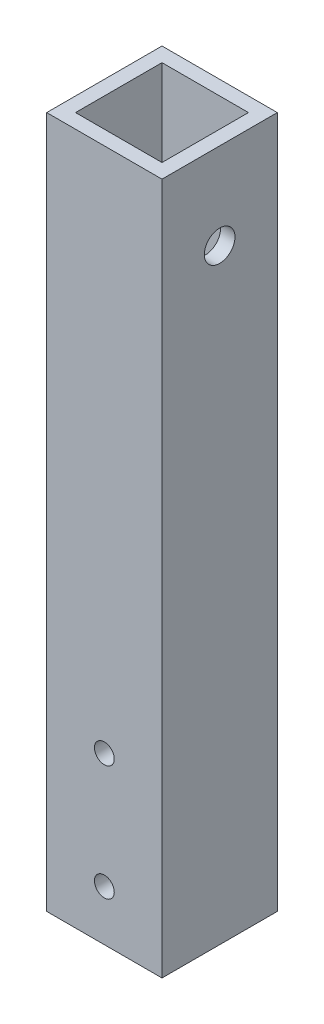
SolidWorks part; units mm, degrees
ref_plane "Front Plane" through (0, 0, 0) normal (0, 0, 1) x (1, 0, 0)
ref_plane "Top Plane" through (0, 0, 0) normal (0, 1, 0) x (1, 0, 0)
ref_plane "Right Plane" through (0, 0, 0) normal (1, 0, 0) x (0, 0, -1)
sketch "Sketch1" plane through (0, 0, 0) normal (0, 1, 0) x (1, 0, 0)
  line L0 (-12.7, 12.7) -> (12.7, 12.7)
  line L1 (-9.525, -9.525) -> (9.525, -9.525)
  line L2 (-9.525, -9.525) -> (-9.525, 9.525)
  line L3 (-9.525, 9.525) -> (9.525, 9.525)
  line L4 (9.525, -9.525) -> (9.525, 9.525)
  line L5 (-9.525, -9.525) -> (9.525, 9.525) construction
  line L6 (-9.525, 9.525) -> (9.525, -9.525) construction
  line L7 (12.7, -12.7) -> (12.7, 12.7)
  line L8 (-12.7, -12.7) -> (12.7, -12.7)
  line L9 (-12.7, -12.7) -> (-12.7, 12.7)
  point P0 (0, 0)
  dimension "D2" = 25.4
  dimension "D1" = 3.175
extrude "Boss-Extrude1" add sketch "Sketch1" along normal blind 152.4
sketch "Sketch2" plane through (0, 0, 12.7) normal (0, 0, 1) x (1, 0, 0)
  line L0 (0, 152.4) -> (0, 0) construction
  line L1 (-12.7, 152.4) -> (12.7, 152.4) construction
  line L2 (-12.7, 0) -> (12.7, 0) construction
  circle A0 centre (0, 11.1125) radius 2.1828
  circle A1 centre (0, 36.5125) radius 2.1828
  dimension "D1" = 4.3656
  dimension "D2" = 4.3656
  dimension "D3" = 25.4
  dimension "D4" = 11.1125
extrude "Cut-Extrude1" cut sketch "Sketch2" against normal through all
sketch "Sketch3" plane through (12.7, 0, 0) normal (1, 0, 0) x (0, 0, -1)
  line L0 (0, 152.4) -> (0, 0) construction
  line L1 (-12.7, 152.4) -> (12.7, 152.4) construction
  circle A0 centre (0, 133.35) radius 3.3734
  dimension "D1" = 6.7469
  dimension "D2" = 19.05
extrude "Cut-Extrude2" cut sketch "Sketch3" against normal blind 154.94
